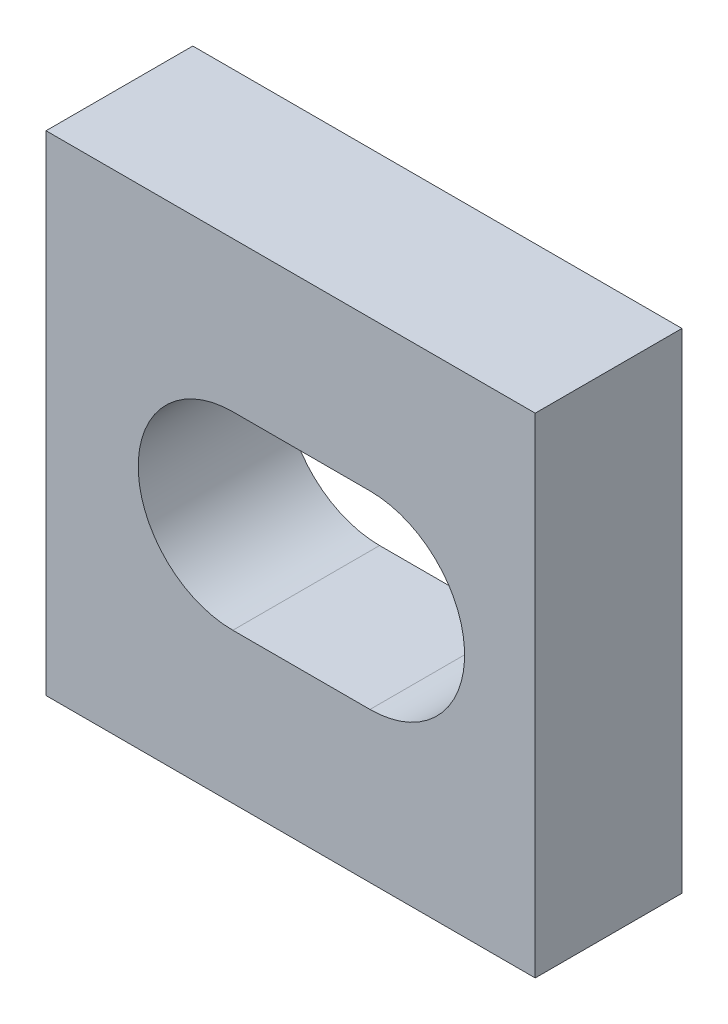
SolidWorks part; units mm, degrees
ref_plane "前视基准面" through (0, 0, 0) normal (0, 0, 1) x (1, 0, 0)
ref_plane "上视基准面" through (0, 0, 0) normal (0, 1, 0) x (1, 0, 0)
ref_plane "右视基准面" through (0, 0, 0) normal (1, 0, 0) x (0, 0, -1)
sketch "草图1" plane through (0, 0, 0) normal (0, 0, 1) x (1, 0, 0)
  line L0 (3.8185, -5) -> (6.6223, -5) construction
  line L1 (0, 0) -> (10, 0)
  line L2 (0, 0) -> (0, -10)
  line L3 (0, -10) -> (10, -10)
  line L4 (10, 0) -> (10, -10)
  line L5 (3.8185, -3.0658) -> (6.6223, -3.0658)
  line L6 (3.8185, -6.9342) -> (6.6223, -6.9342)
  arc A0 (3.8185, -3.0658) -> (3.8185, -6.9342) centre (3.8185, -5) ccw
  arc A1 (6.6223, -6.9342) -> (6.6223, -3.0658) centre (6.6223, -5) ccw
  point P7 (5.2204, -5)
extrude "凸台-拉伸1" add sketch "草图1" along normal blind 3
ref_plane "基准面1" through (0, -5, 0) normal (0, -1, 0) x (-1, 0, 0)
